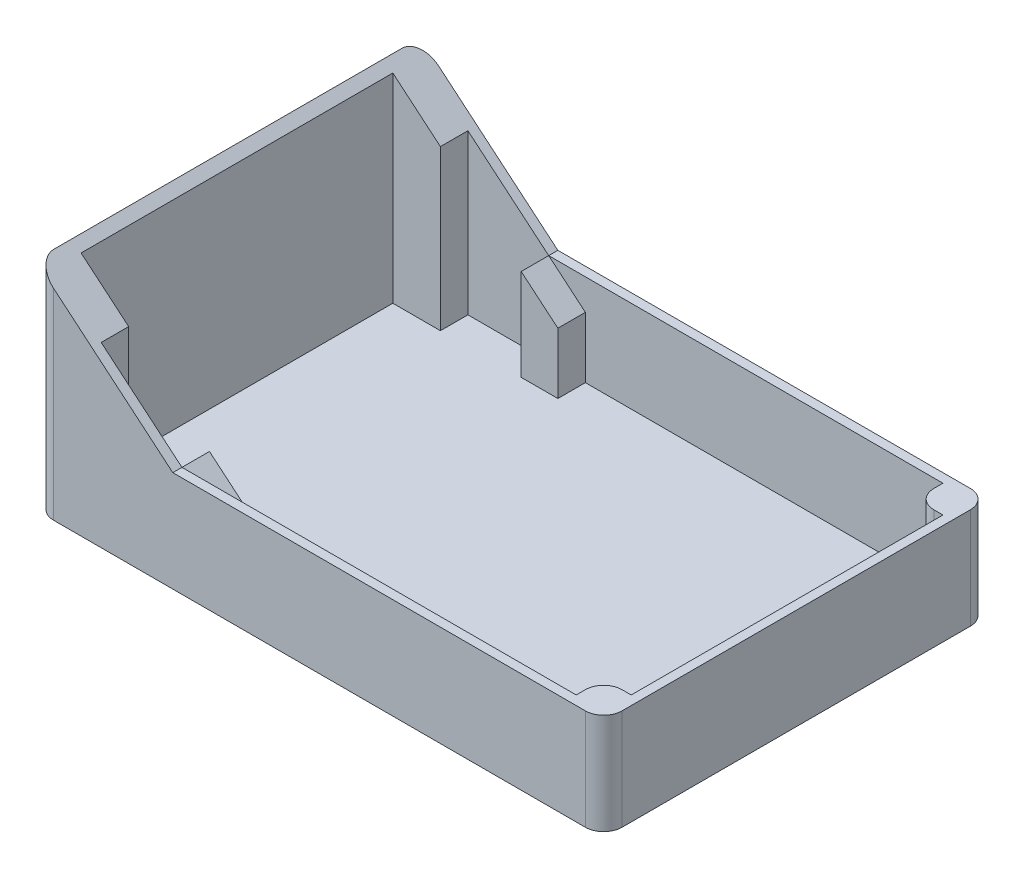
SolidWorks part; units mm, degrees
ref_plane "Front Plane" through (0, 0, 0) normal (0, 0, 1) x (1, 0, 0)
ref_plane "Top Plane" through (0, 0, 0) normal (0, 1, 0) x (1, 0, 0)
ref_plane "Right Plane" through (0, 0, 0) normal (1, 0, 0) x (0, 0, -1)
sketch "Sketch1" plane through (0, 0, 0) normal (0, 1, 0) x (1, 0, 0)
  line L1 (-60, 40) -> (60, 40)
  line L2 (-60, 40) -> (-60, -40)
  line L3 (-60, -40) -> (60, -40)
  line L4 (60, 40) -> (60, -40)
  line L5 (-60, 40) -> (60, -40) construction
  line L6 (-60, -40) -> (60, 40) construction
  point P0 (0, 0)
  dimension "D1" = 120
  dimension "D2" = 80
extrude "Extrude-Thin1" add sketch "Sketch1" along normal blind 20 thin thin type one direction wall 2
sketch "Sketch2" plane through (0, 0, 0) normal (0, -1, 0) x (1, 0, 0)
  line L4 (62, -42) -> (62, 42)
  line L5 (62, 42) -> (-62, 42)
  line L6 (-62, 42) -> (-62, -42)
  line L7 (-62, -42) -> (62, -42)
  line L8 (62, -42) -> (62, 42)
  line L9 (62, 42) -> (-62, 42)
  line L10 (-62, 42) -> (-62, -42)
  line L11 (-62, -42) -> (62, -42)
  dimension "D1" = 0
extrude "Boss-Extrude1" add sketch "Sketch2" along normal blind 2 contours L8 L9 L10 L11
sketch "Sketch3" plane through (0, 0, -40) normal (0, 0, 1) x (1, 0, 0)
  line L2 (-24, 13.2872) -> (-24, -2)
  line L3 (-24, -2) -> (-32, -2)
  line L4 (-32, 20) -> (-32, -2)
  line L5 (-62, 20) -> (-62, -2) construction
  line L6 (-62, -2) -> (62, -2) construction
  line L7 (-32, 20) -> (-24, 13.2872)
  dimension "D1" = 8
  dimension "D3" = 30
extrude "Boss-Extrude2" add sketch "Sketch3" along normal blind 6
ref_plane "Plane1" through (0, 0, 0) normal (0, 0, -1) x (-1, 0, 0)
sketch "Sketch9" plane through (0, 20, 0) normal (0, 1, 0) x (1, 0, 0)
  line L1 (60, 40) -> (54, 40)
  line L2 (60, 40) -> (60, 34)
  line L3 (60, 34) -> (54, 34)
  line L4 (54, 40) -> (54, 34)
  line L5 (60, -40) -> (54, -40)
  line L6 (60, -40) -> (60, -34)
  line L7 (60, -34) -> (54, -34)
  line L8 (54, -40) -> (54, -34)
  dimension "D1" = 6
  dimension "D2" = 6
  dimension "D3" = 6
  dimension "D4" = 6
extrude "Boss-Extrude7" add sketch "Sketch9" against normal up to surface (20 mm away) up to face at (-14, 0, -18.5)
sketch "Sketch10" plane through (0, 0, -42) normal (0, 0, -1) x (-1, 0, 0)
  line L0 (62, 20) -> (62, 45.173)
  line L1 (62, 45.173) -> (32, 20)
  line L2 (-62, 20) -> (62, 20) construction
  line L3 (32, 20) -> (62, 20)
  dimension "D1" = 40
extrude "Boss-Extrude8" add sketch "Sketch10" against normal blind 2
sketch "Sketch11" plane through (0, 0, -42) normal (0, 0, -1) x (-1, 0, 0)
  line L1 (62, 45.173) -> (32, 20) construction
  line L4 (62, 45.173) -> (49.619, 34.7841)
  line L5 (62, 45.173) -> (62, -2)
  line L6 (62, -2) -> (-62, -2) construction
  line L7 (49.619, -2) -> (62, -2)
  line L8 (49.619, 34.7841) -> (49.619, -2)
  line L9 (62, 45.173) -> (62, -2) construction
  dimension "D1" = 23
extrude "Boss-Extrude9" add sketch "Sketch11" against normal blind 6 from offset 2 offset against normal yes
mirror "Mirror1" about plane through (0, 0, 0) normal (0, 0, -1) of "Boss-Extrude9", "Boss-Extrude8", "Boss-Extrude2"
sketch "Sketch12" plane through (0, 0, -34) normal (0, 0, 1) x (1, 0, 0)
  line L0 (-62, 20) -> (-62, 45.173)
  line L1 (-62, 20) -> (-60, 20)
  line L2 (-60, 20) -> (-60, 43.4948)
  line L3 (-62, 45.173) -> (-49.619, 34.7841) construction
  line L4 (-60, 43.4948) -> (-62, 45.173)
extrude "Boss-Extrude10" add sketch "Sketch12" along normal up to surface (68 mm away) up to face at (-57.2063, 19.9929, 34)
fillet "Fillet1" radius 4 6 edges at (62, 9, 42) (-62, 21.5865, 42) (-62, 21.5865, -42) (62, 9, -42) (54, 10, -34) (54, 10, 34)
